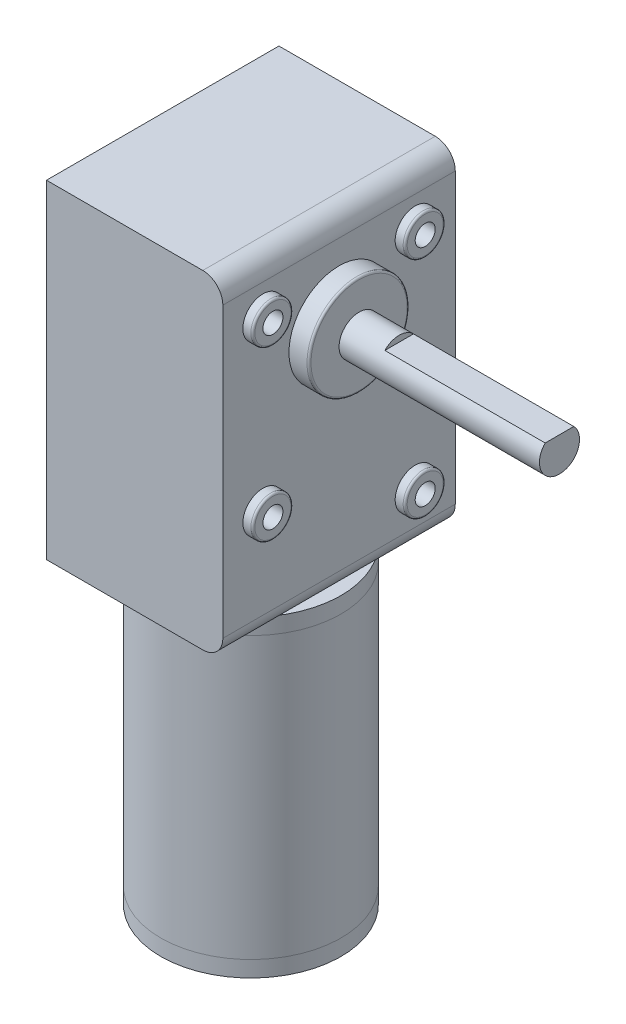
SolidWorks part; units mm, degrees
ref_plane "Front Plane" through (0, 0, 0) normal (0, 0, 1) x (1, 0, 0)
ref_plane "Top Plane" through (0, 0, 0) normal (0, 1, 0) x (1, 0, 0)
ref_plane "Right Plane" through (0, 0, 0) normal (1, 0, 0) x (0, 0, -1)
sketch "Sketch1" plane through (0, 0, 0) normal (0, 1, 0) x (1, 0, 0)
  circle A0 centre (0, 0) radius 22.5
  dimension "D1" = 45
extrude "Boss-Extrude1" add sketch "Sketch1" along normal blind 4
sketch "Sketch2" plane through (0, 4, 0) normal (0, 1, 0) x (1, 0, 0)
  circle A0 centre (0, 0) radius 22.5
  circle A1 centre (0, 0) radius 22.5 construction
extrude "Boss-Extrude2" add sketch "Sketch2" along normal blind 70 separate body
sketch "Sketch3" plane through (0, 74, 0) normal (0, 1, 0) x (1, 0, 0)
  circle A0 centre (0, 0) radius 22.5
  circle A1 centre (0, 0) radius 22.5 construction
extrude "Boss-Extrude3" add sketch "Sketch3" along normal blind 4 separate body
sketch "Sketch4" plane through (0, 78, 0) normal (0, 1, 0) x (1, 0, 0)
  line L1 (-22, 29) -> (22, 29)
  line L2 (-22, 29) -> (-22, -29)
  line L3 (-22, -29) -> (22, -29)
  line L4 (22, 29) -> (22, -29)
  point P4 (0, 29)
  point P5 (22, 0)
  dimension "D1" = 58
  dimension "D2" = 44
extrude "Boss-Extrude4" add sketch "Sketch4" along normal blind 82 separate body
sketch "Sketch5" plane through (0, 160, 0) normal (0, 1, 0) x (1, 0, 0)
  line L0 (-22, -29) -> (22, -29) construction
  line L1 (-22, 29) -> (-19, 29)
  line L2 (-22, 29) -> (-22, -29)
  line L3 (-22, -29) -> (-19, -29)
  line L4 (-19, 29) -> (-19, -29)
  dimension "D1" = 3
extrude "Cut-Extrude1" cut sketch "Sketch5" against normal blind 82
sketch "Sketch6" plane through (0, 160, 0) normal (0, 1, 0) x (1, 0, 0)
  line L0 (-22, 29) -> (-19, 29)
  line L1 (-22, 29) -> (-22, -29)
  line L2 (-22, -29) -> (-19, -29)
  line L3 (-19, 29) -> (-19, -29)
  line L4 (-19, -29) -> (-19, 29) construction
  line L5 (22, 29) -> (-19, 29) construction
  line L6 (-19, -29) -> (22, -29) construction
  dimension "D1" = 3
extrude "Boss-Extrude5" add sketch "Sketch6" against normal blind 82 separate body
sketch "Sketch7" plane through (22, 0, 0) normal (1, 0, 0) x (0, 0, -1)
  line L0 (0, 160) -> (0, 0) construction
  line L1 (-29, 160) -> (29, 160) construction
  circle A0 centre (0, 136.5) radius 12.5
  dimension "D1" = 23.5
  dimension "D2" = 25
extrude "Boss-Extrude6" add sketch "Sketch7" along normal blind 5 and the other way blind 49
sketch "Sketch8" plane through (27, 0, 0) normal (1, 0, 0) x (0, 0, -1)
  circle A0 centre (0, 136.5) radius 5
  dimension "D1" = 10
extrude "Boss-Extrude7" add sketch "Sketch8" along normal blind 50
sketch "Sketch9" plane through (77, 0, 0) normal (1, 0, 0) x (0, 0, -1)
  line L0 (-3.5707, 140) -> (3.5707, 140)
  line L1 (0, 136.5) -> (0, 140) construction
  line L2 (-3.5707, 131.5) -> (3.5707, 131.5) construction
  arc A0 (3.5707, 140) -> (-3.5707, 140) centre (0, 136.5) ccw
  circle A1 centre (0, 136.5) radius 5 construction
  circle A3 centre (0, 136.5) radius 5 construction
  dimension "D1" = 8.5
extrude "Cut-Extrude2" cut sketch "Sketch9" against normal blind 40
sketch "Sketch10" plane through (22, 0, 0) normal (1, 0, 0) x (0, 0, -1)
  line L0 (-19, 160) -> (-19, 78) construction
  line L1 (-29, 160) -> (29, 160) construction
  line L2 (22.5, 78) -> (-22.5, 78) construction
  line L3 (0, 160) -> (0, 78) construction
  line L4 (19, 160) -> (19, 78) construction
  line L5 (-29, 78) -> (29, 78) construction
  circle A0 centre (-19, 147.4389) radius 5
  circle A1 centre (-19, 105.4389) radius 5
  circle A2 centre (19, 147.4389) radius 5
  circle A3 centre (19, 91.43) radius 5
  circle A4 centre (0, 136.5) radius 12.5 construction
  dimension "D2" = 42
  dimension "D3" = 10
  dimension "D4" = 45.07
  dimension "D6" = 19
  dimension "D1" = 38
  dimension "D5" = 40.5
extrude "Boss-Extrude8" add sketch "Sketch10" along normal blind 2.5 and the other way blind 46.5
sketch "Sketch11" plane through (24.5, 0, 0) normal (1, 0, 0) x (0, 0, -1)
  circle A0 centre (-19, 147.4389) radius 2.5
  circle A1 centre (19, 147.4389) radius 2.5
  circle A2 centre (19, 91.43) radius 2.5
  circle A3 centre (-19, 105.4389) radius 2.5
  dimension "D1" = 5
extrude "Cut-Extrude3" cut sketch "Sketch11" against normal blind 8
fillet "Fillet1" radius 5 2 edges at (22, 78, 0) (22, 160, 0)
fillet "Fillet2" radius 0.5 10 edges at (-24.5, 91.43, -24) (-24.5, 105.4389, 14) (-24.5, 147.4389, 14) (-27, 136.5, -12.5) (-24.5, 147.4389, -24) (27, 136.5, -12.5) (24.5, 147.4389, 14) (24.5, 105.4389, 14) (24.5, 147.4389, -24) (24.5, 91.43, -24)
sketch "Sketch12" plane through (0, 140, 0) normal (0, 1, 0) x (1, 0, 0)
  line L0 (27, -5) -> (77, -5) construction
  line L1 (77, 5) -> (47, 5)
  line L2 (77, 5) -> (77, -5)
  line L3 (77, -5) -> (47, -5)
  line L4 (47, 5) -> (47, -5)
  dimension "D1" = 30
extrude "Cut-Extrude4" [suppressed] cut sketch "Sketch12" against normal through all
